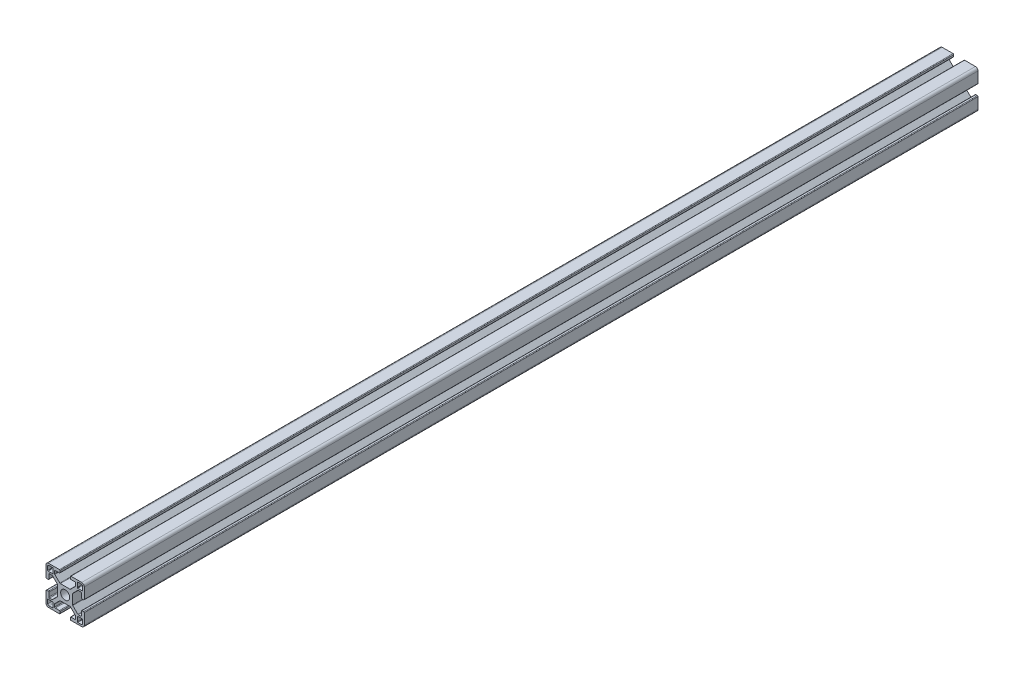
SolidWorks part; units mm, degrees
ref_plane "Front Plane" through (0, 0, 0) normal (0, 0, 1) x (1, 0, 0)
ref_plane "Top Plane" through (0, 0, 0) normal (0, 1, 0) x (1, 0, 0)
ref_plane "Right Plane" through (0, 0, 0) normal (1, 0, 0) x (0, 0, -1)
sketch "Sketch1" plane through (0, 0, 0) normal (0, 0, 1) x (1, 0, 0)
  line L0 (3.9799, -2.4733) -> (3.1981, -1.4942) construction
  line L1 (1.4942, -3.1981) -> (2.4733, -3.9799) construction
  line L2 (-2.4733, -3.9799) -> (-1.4942, -3.1981) construction
  line L3 (-3.1981, -1.4942) -> (-3.9799, -2.4733) construction
  line L4 (-3.9799, 2.4733) -> (-3.1981, 1.4942) construction
  line L5 (-1.4942, 3.1981) -> (-2.4733, 3.9799) construction
  line L6 (2.4733, 3.9799) -> (1.4942, 3.1981) construction
  line L7 (3.1981, 1.4942) -> (3.9799, 2.4733) construction
  line L8 (-12.6999, -13.6999) -> (-9.881, -13.6999)
  line L9 (-13.6999, -9.881) -> (-13.6999, -12.6999)
  line L10 (-9.88, -9.5) -> (-13.3189, -9.5)
  line L11 (-9.5, -13.3189) -> (-9.5, -9.88)
  line L12 (13.6999, -12.6999) -> (13.6999, -9.881)
  line L13 (9.881, -13.6999) -> (12.6999, -13.6999)
  line L14 (9.5, -9.88) -> (9.5, -13.3189)
  line L15 (13.3189, -9.5) -> (9.88, -9.5)
  line L16 (9.88, 9.5) -> (13.3189, 9.5)
  line L17 (9.5, 13.3189) -> (9.5, 9.88)
  line L18 (12.6999, 13.6999) -> (9.881, 13.6999)
  line L19 (13.6999, 9.881) -> (13.6999, 12.6999)
  line L20 (-13.6999, 12.6999) -> (-13.6999, 9.881)
  line L21 (-9.881, 13.6999) -> (-12.6999, 13.6999)
  line L22 (-9.5, 9.88) -> (-9.5, 13.3189)
  line L23 (-13.3189, 9.5) -> (-9.88, 9.5)
  line L24 (14.4999, -4) -> (13.2425, -4)
  line L25 (12.7425, -4.5) -> (12.7425, -7.7325)
  line L26 (12.2428, -8.25) -> (10.2602, -8.25)
  line L27 (9.9066, -8.1035) -> (5.9811, -4.178)
  line L28 (5.8347, -3.8245) -> (5.8347, -1.0125)
  line L29 (5.8347, -1.0125) -> (5.3247, -0.0625) construction
  line L30 (5.3247, -0.0625) -> (5.8347, 0.8875) construction
  line L31 (5.8347, 0.8875) -> (5.8347, 3.8245)
  line L32 (5.9811, 4.178) -> (9.9066, 8.1035)
  line L33 (10.2602, 8.25) -> (12.2428, 8.25)
  line L34 (12.7425, 7.7325) -> (12.7425, 4.5)
  line L35 (13.2425, 4) -> (14.4999, 4)
  line L36 (14.9999, 4.5) -> (14.9999, 12.9999)
  line L37 (12.9999, 14.9999) -> (4.5, 14.9999)
  line L38 (4, 14.4999) -> (4, 13.2425)
  line L39 (4.5, 12.7425) -> (7.7325, 12.7425)
  line L40 (8.25, 12.2428) -> (8.25, 10.2602)
  line L41 (8.1035, 9.9066) -> (4.178, 5.9811)
  line L42 (3.8245, 5.8347) -> (0.95, 5.8347)
  line L43 (0.95, 5.8347) -> (0, 5.3247) construction
  line L44 (0, 5.3247) -> (-0.95, 5.8347) construction
  line L45 (-0.95, 5.8347) -> (-3.8245, 5.8347)
  line L46 (-4.178, 5.9811) -> (-8.1035, 9.9066)
  line L47 (-8.25, 10.2602) -> (-8.25, 12.2428)
  line L48 (-7.7325, 12.7425) -> (-4.5, 12.7425)
  line L49 (-4, 13.2425) -> (-4, 14.4999)
  line L50 (-4.5, 14.9999) -> (-12.9999, 14.9999)
  line L51 (-14.9999, 12.9999) -> (-14.9999, 4.5)
  line L52 (-14.4999, 4) -> (-13.2425, 4)
  line L53 (-12.7425, 4.5) -> (-12.7425, 7.7325)
  line L54 (-12.2428, 8.25) -> (-10.2602, 8.25)
  line L55 (-9.9066, 8.1035) -> (-5.9811, 4.178)
  line L56 (-5.8347, 3.8245) -> (-5.8347, 0.8875)
  line L57 (-5.8347, 0.8875) -> (-5.3247, -0.0625) construction
  line L58 (-5.3247, -0.0625) -> (-5.8347, -1.0125) construction
  line L59 (-5.8347, -1.0125) -> (-5.8347, -3.8245)
  line L60 (-5.9811, -4.178) -> (-9.9066, -8.1035)
  line L61 (-10.2602, -8.25) -> (-12.2428, -8.25)
  line L62 (-12.7425, -7.7325) -> (-12.7425, -4.5)
  line L63 (-13.2425, -4) -> (-14.4999, -4)
  line L64 (-14.9999, -4.5) -> (-14.9999, -12.9999)
  line L65 (-12.9999, -14.9999) -> (-4.5, -14.9999)
  line L66 (-4, -14.4999) -> (-4, -13.2425)
  line L67 (-4.5, -12.7425) -> (-7.7325, -12.7425)
  line L68 (-8.25, -12.2428) -> (-8.25, -10.2602)
  line L69 (-8.1035, -9.9066) -> (-4.178, -5.9811)
  line L70 (-3.8245, -5.8347) -> (-0.95, -5.8347)
  line L71 (-0.95, -5.8347) -> (0, -5.3247) construction
  line L72 (0, -5.3247) -> (0.95, -5.8347) construction
  line L73 (0.95, -5.8347) -> (3.8245, -5.8347)
  line L74 (4.178, -5.9811) -> (8.1035, -9.9066)
  line L75 (8.25, -10.2602) -> (8.25, -12.2428)
  line L76 (7.7325, -12.7425) -> (4.5, -12.7425)
  line L77 (4, -13.2425) -> (4, -14.4999)
  line L78 (4.5, -14.9999) -> (12.9999, -14.9999)
  line L79 (14.9999, -12.9999) -> (14.9999, -4.5)
  line L80 (-5.8347, -1.0125) -> (-5.8347, 0.8875)
  line L81 (-0.95, 5.8347) -> (0.95, 5.8347)
  line L82 (5.8347, 0.8875) -> (5.8347, -1.0125)
  line L83 (-0.95, -5.8347) -> (0.95, -5.8347)
  arc A0 (2.4733, -3.9799) -> (3.9799, -2.4733) centre (3.1422, -3.1422) ccw construction
  arc A1 (-1.4942, -3.1981) -> (1.4942, -3.1981) centre (0, 0) ccw construction
  arc A2 (-3.9799, -2.4733) -> (-2.4733, -3.9799) centre (-3.1422, -3.1422) ccw construction
  arc A3 (-3.1981, 1.4942) -> (-3.1981, -1.4942) centre (0, 0) ccw construction
  arc A4 (-2.4733, 3.9799) -> (-3.9799, 2.4733) centre (-3.1422, 3.1422) ccw construction
  arc A5 (1.4942, 3.1981) -> (-1.4942, 3.1981) centre (0, 0) ccw construction
  arc A6 (3.9799, 2.4733) -> (2.4733, 3.9799) centre (3.1422, 3.1422) ccw construction
  arc A7 (3.1981, -1.4942) -> (3.1981, 1.4942) centre (0, 0) ccw construction
  arc A8 (-13.6999, -12.6999) -> (-12.6999, -13.6999) centre (-12.6999, -12.6999) ccw
  arc A9 (-13.3189, -9.5) -> (-13.6999, -9.881) centre (-13.3189, -9.881) ccw
  arc A10 (-9.5, -9.88) -> (-9.88, -9.5) centre (-9.88, -9.88) ccw
  arc A11 (-9.881, -13.6999) -> (-9.5, -13.3189) centre (-9.881, -13.3189) ccw
  arc A12 (12.6999, -13.6999) -> (13.6999, -12.6999) centre (12.6999, -12.6999) ccw
  arc A13 (9.5, -13.3189) -> (9.881, -13.6999) centre (9.881, -13.3189) ccw
  arc A14 (9.88, -9.5) -> (9.5, -9.88) centre (9.88, -9.88) ccw
  arc A15 (13.6999, -9.881) -> (13.3189, -9.5) centre (13.3189, -9.881) ccw
  arc A16 (9.5, 9.88) -> (9.88, 9.5) centre (9.88, 9.88) ccw
  arc A17 (9.881, 13.6999) -> (9.5, 13.3189) centre (9.881, 13.3189) ccw
  arc A18 (13.6999, 12.6999) -> (12.6999, 13.6999) centre (12.6999, 12.6999) ccw
  arc A19 (13.3189, 9.5) -> (13.6999, 9.881) centre (13.3189, 9.881) ccw
  arc A20 (14.9999, -4.5) -> (14.4999, -4) centre (14.4999, -4.5) ccw
  arc A21 (13.2425, -4) -> (12.7425, -4.5) centre (13.2425, -4.5) ccw
  arc A22 (12.2428, -8.25) -> (12.7425, -7.7325) centre (12.2428, -7.75) ccw
  arc A23 (9.9066, -8.1035) -> (10.2602, -8.25) centre (10.2602, -7.75) ccw
  arc A24 (5.8347, -3.8245) -> (5.9811, -4.178) centre (6.3347, -3.8245) ccw
  arc A25 (5.9811, 4.178) -> (5.8347, 3.8245) centre (6.3347, 3.8245) ccw
  arc A26 (10.2602, 8.25) -> (9.9066, 8.1035) centre (10.2602, 7.75) ccw
  arc A27 (12.7425, 7.7325) -> (12.2428, 8.25) centre (12.2428, 7.75) ccw
  arc A28 (12.7425, 4.5) -> (13.2425, 4) centre (13.2425, 4.5) ccw
  arc A29 (14.4999, 4) -> (14.9999, 4.5) centre (14.4999, 4.5) ccw
  arc A30 (14.9999, 12.9999) -> (12.9999, 14.9999) centre (12.9999, 12.9999) ccw
  arc A31 (4.5, 14.9999) -> (4, 14.4999) centre (4.5, 14.4999) ccw
  arc A32 (4, 13.2425) -> (4.5, 12.7425) centre (4.5, 13.2425) ccw
  arc A33 (8.25, 12.2428) -> (7.7325, 12.7425) centre (7.75, 12.2428) ccw
  arc A34 (8.1035, 9.9066) -> (8.25, 10.2602) centre (7.75, 10.2602) ccw
  arc A35 (3.8245, 5.8347) -> (4.178, 5.9811) centre (3.8245, 6.3347) ccw
  arc A36 (-4.178, 5.9811) -> (-3.8245, 5.8347) centre (-3.8245, 6.3347) ccw
  arc A37 (-8.25, 10.2602) -> (-8.1035, 9.9066) centre (-7.75, 10.2602) ccw
  arc A38 (-7.7325, 12.7425) -> (-8.25, 12.2428) centre (-7.75, 12.2428) ccw
  arc A39 (-4.5, 12.7425) -> (-4, 13.2425) centre (-4.5, 13.2425) ccw
  arc A40 (-4, 14.4999) -> (-4.5, 14.9999) centre (-4.5, 14.4999) ccw
  arc A41 (-12.9999, 14.9999) -> (-14.9999, 12.9999) centre (-12.9999, 12.9999) ccw
  arc A42 (-14.9999, 4.5) -> (-14.4999, 4) centre (-14.4999, 4.5) ccw
  arc A43 (-13.2425, 4) -> (-12.7425, 4.5) centre (-13.2425, 4.5) ccw
  arc A44 (-12.2428, 8.25) -> (-12.7425, 7.7325) centre (-12.2428, 7.75) ccw
  arc A45 (-9.9066, 8.1035) -> (-10.2602, 8.25) centre (-10.2602, 7.75) ccw
  arc A46 (-5.8347, 3.8245) -> (-5.9811, 4.178) centre (-6.3347, 3.8245) ccw
  arc A47 (-5.9811, -4.178) -> (-5.8347, -3.8245) centre (-6.3347, -3.8245) ccw
  arc A48 (-10.2602, -8.25) -> (-9.9066, -8.1035) centre (-10.2602, -7.75) ccw
  arc A49 (-12.7425, -7.7325) -> (-12.2428, -8.25) centre (-12.2428, -7.75) ccw
  arc A50 (-12.7425, -4.5) -> (-13.2425, -4) centre (-13.2425, -4.5) ccw
  arc A51 (-14.4999, -4) -> (-14.9999, -4.5) centre (-14.4999, -4.5) ccw
  arc A52 (-14.9999, -12.9999) -> (-12.9999, -14.9999) centre (-12.9999, -12.9999) ccw
  arc A53 (-4.5, -14.9999) -> (-4, -14.4999) centre (-4.5, -14.4999) ccw
  arc A54 (-4, -13.2425) -> (-4.5, -12.7425) centre (-4.5, -13.2425) ccw
  arc A55 (-8.25, -12.2428) -> (-7.7325, -12.7425) centre (-7.75, -12.2428) ccw
  arc A56 (-8.1035, -9.9066) -> (-8.25, -10.2602) centre (-7.75, -10.2602) ccw
  arc A57 (-3.8245, -5.8347) -> (-4.178, -5.9811) centre (-3.8245, -6.3347) ccw
  arc A58 (4.178, -5.9811) -> (3.8245, -5.8347) centre (3.8245, -6.3347) ccw
  arc A59 (8.25, -10.2602) -> (8.1035, -9.9066) centre (7.75, -10.2602) ccw
  arc A60 (7.7325, -12.7425) -> (8.25, -12.2428) centre (7.75, -12.2428) ccw
  arc A61 (4.5, -12.7425) -> (4, -13.2425) centre (4.5, -13.2425) ccw
  arc A62 (4, -14.4999) -> (4.5, -14.9999) centre (4.5, -14.4999) ccw
  arc A63 (12.9999, -14.9999) -> (14.9999, -12.9999) centre (12.9999, -12.9999) ccw
  arc A64 (-12.6999, 13.6999) -> (-13.6999, 12.6999) centre (-12.6999, 12.6999) ccw
  arc A65 (-9.5, 13.3189) -> (-9.881, 13.6999) centre (-9.881, 13.3189) ccw
  arc A66 (-9.88, 9.5) -> (-9.5, 9.88) centre (-9.88, 9.88) ccw
  arc A67 (-13.6999, 9.881) -> (-13.3189, 9.5) centre (-13.3189, 9.881) ccw
  circle A68 centre (0, 0) radius 3.53
extrude "Boss-Extrude1" add sketch "Sketch1" along normal mid plane 700
